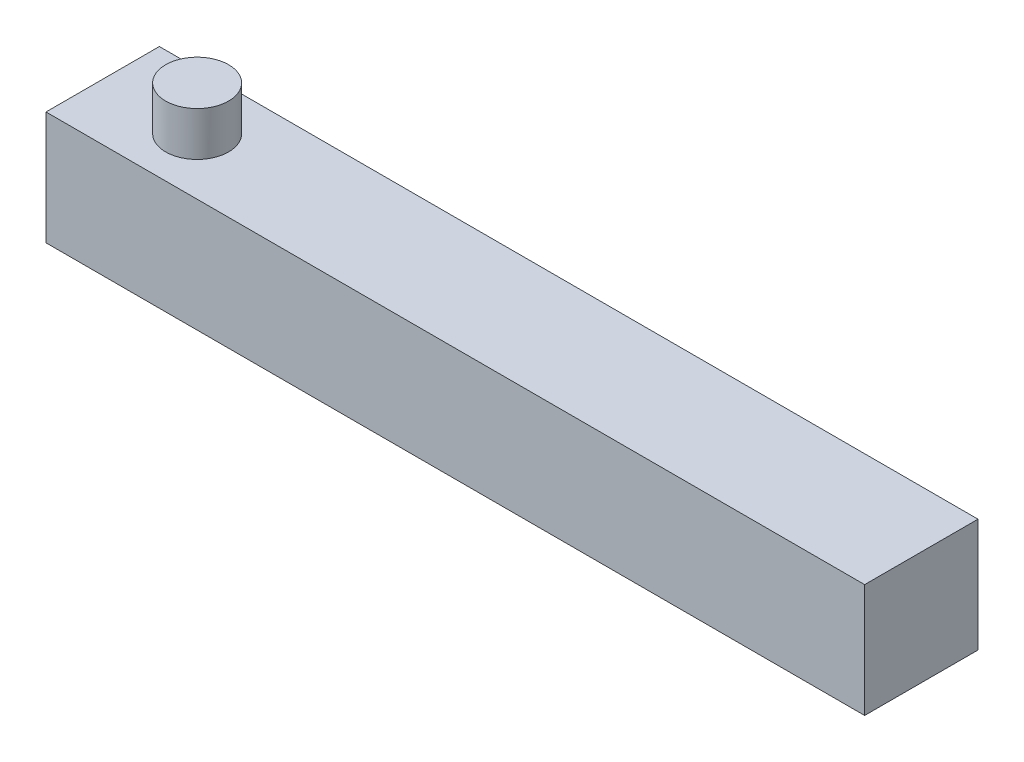
SolidWorks part; units mm, degrees
ref_plane "前基準面" through (0, 0, 0) normal (0, 0, 1) x (1, 0, 0)
ref_plane "上基準面" through (0, 0, 0) normal (0, 1, 0) x (1, 0, 0)
ref_plane "右基準面" through (0, 0, 0) normal (1, 0, 0) x (0, 0, -1)
ref_plane "平面1"
sketch "草圖1" plane through (0, 0, 0) normal (0, 1, 0) x (-1, 0, 0)
  line L0 (32.5, -4.5) -> (-32.5, -4.5)
  line L1 (-32.5, -4.5) -> (-32.5, 4.5)
  line L2 (-32.5, 4.5) -> (32.5, 4.5)
  line L3 (32.5, 4.5) -> (32.5, -4.5)
  dimension "D1" = 65
  dimension "D2" = 9
extrude "擠出1" add sketch "草圖1" along normal blind 9
sketch "草圖2" plane through (0, 9, 0) normal (0, 1, 0) x (-1, 0, 0)
  circle A0 centre (25, 0) radius 2.5
  circle A1 centre (-25, 0) radius 2.5
  dimension "D3" = 5
  dimension "D4" = 5
  dimension "D1" = 25
  dimension "D2" = 25
extrude "擠出2" add sketch "草圖2" along normal blind 3.5 contours A1 | A0
sketch "草圖3" plane through (0, 9, 0) normal (0, 1, 0) x (-1, 0, 0)
  circle A0 centre (-25, 0) radius 2.5
extrude "擠出3" cut sketch "草圖3" along normal blind 10
